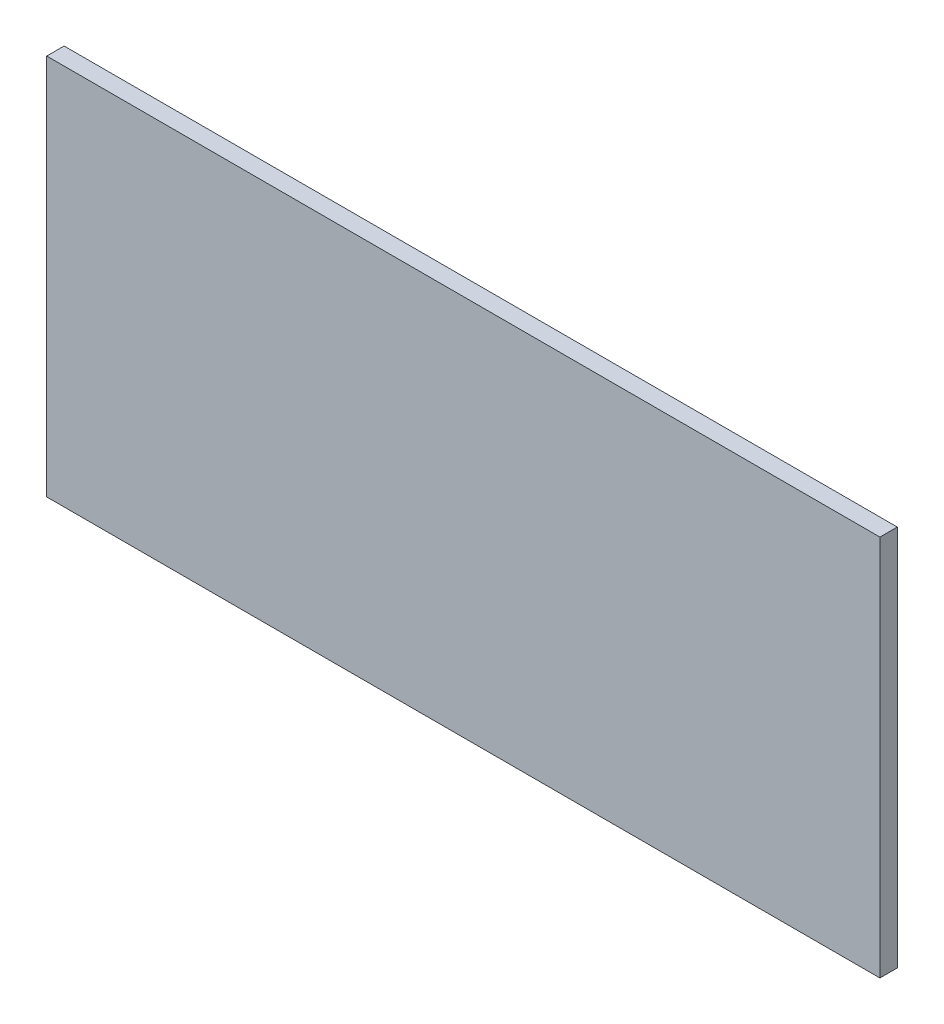
SolidWorks part; units mm, degrees
ref_plane "Front Plane" through (0, 0, 0) normal (0, 0, 1) x (1, 0, 0)
ref_plane "Top Plane" through (0, 0, 0) normal (0, 1, 0) x (1, 0, 0)
ref_plane "Right Plane" through (0, 0, 0) normal (1, 0, 0) x (0, 0, -1)
sketch "Sketch1" plane through (0, 0, 0) normal (0, 0, 1) x (1, 0, 0)
  line L1 (0, 0) -> (304.8, 0)
  line L2 (0, 0) -> (0, 139.7)
  line L3 (0, 139.7) -> (304.8, 139.7)
  line L4 (304.8, 0) -> (304.8, 139.7)
  dimension "D1" = 304.8
  dimension "D2" = 139.7
extrude "Boss-Extrude1" add sketch "Sketch1" along normal blind 6.35
